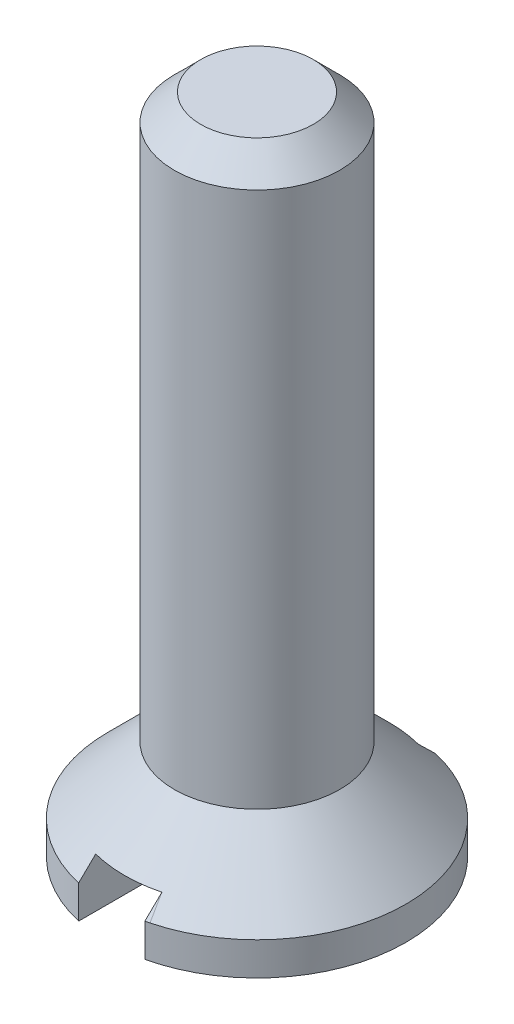
SolidWorks part; units mm, degrees
ref_plane "Спереди" through (0, 0, 0) normal (0, 0, 1) x (1, 0, 0)
ref_plane "Сверху" through (0, 0, 0) normal (0, 1, 0) x (1, 0, 0)
ref_plane "Справа" through (0, 0, 0) normal (1, 0, 0) x (0, 0, -1)
sketch "Эскиз1" plane through (0, 0, 0) normal (0, 0, 1) x (1, 0, 0)
  line L0 (0, 0) -> (-2.25, 0)
  line L1 (-2.25, 0) -> (-2.25, 0.5)
  line L2 (-2.25, 0.5) -> (-1.25, 1.5)
  line L3 (-1.25, 1.5) -> (-1.25, 10)
  line L4 (-1.25, 10) -> (0, 10)
  line L5 (0, 10) -> (0, 0)
  line L6 (-1.25, 1.5) -> (0, 1.5) construction
  dimension "D1" = 10
  dimension "D2" = 2.25
  dimension "D3" = 1.25
  dimension "D4" = 45
  dimension "D5" = 1.5
revolve "Повернуть1" add sketch "Эскиз1" angle 360 about L5
sketch "Эскиз2" plane through (0, 0, 0) normal (0, 0, 1) x (1, 0, 0)
  line L0 (-2.25, 0) -> (2.25, 0) construction
  line L1 (-0.5, 0) -> (0.5, 0)
  line L2 (-0.5, 0) -> (-0.5, 0.75)
  line L3 (-0.5, 0.75) -> (0.5, 0.75)
  line L4 (0.5, 0) -> (0.5, 0.75)
  dimension "D1" = 0.75
  dimension "D2" = 1
extrude "Вырез-Вытянуть1" cut sketch "Эскиз2" against normal mid plane 20
chamfer "Фаска1" distance 0.4 angle 45 1 edges at (-1.25, 10, 0)
